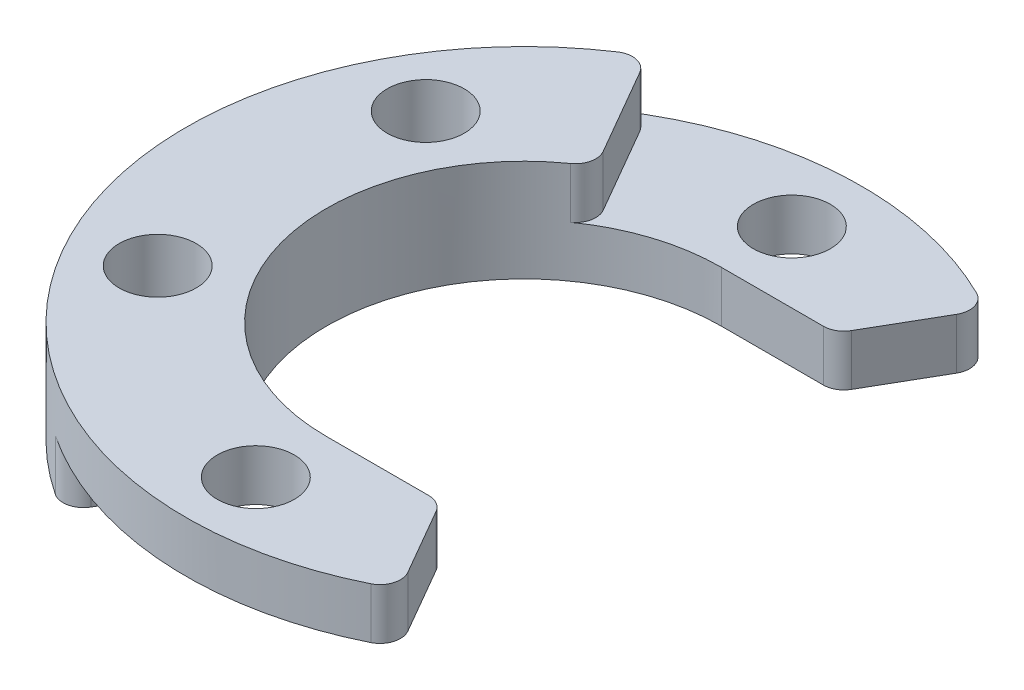
SolidWorks part; units mm, degrees
ref_plane "Front Plane" through (0, 0, 0) normal (0, 0, 1) x (1, 0, 0)
ref_plane "Top Plane" through (0, 0, 0) normal (0, 1, 0) x (1, 0, 0)
ref_plane "Right Plane" through (0, 0, 0) normal (1, 0, 0) x (0, 0, -1)
sketch "Sketch1" plane through (0, 0, 0) normal (0, 1, 0) x (1, 0, 0)
  circle A0 centre (0, 0) radius 42.0965
  circle A1 centre (0, 0) radius 24.5992
  circle A2 centre (0, 33.3931) radius 4.8013
  circle A3 centre (28.9193, 16.6965) radius 4.8013
  circle A4 centre (28.9193, -16.6965) radius 4.8013
  circle A5 centre (0, -33.3931) radius 4.8013
  circle A6 centre (-28.9193, -16.6965) radius 4.8013
  circle A7 centre (-28.9193, 16.6965) radius 4.8013
extrude "Extrude1" add sketch "Sketch1" along normal blind 12.7
sketch "Sketch3" plane through (0, 12.7, 0) normal (0, 1, 0) x (1, 0, 0)
  line L0 (0, 0) -> (28.179, 48.8074)
  line L1 (28.179, 48.8074) -> (52.0996, 15.1016)
  line L2 (52.0996, 15.1016) -> (29.4022, -50.9261)
  line L3 (29.4022, -50.9261) -> (0, 0)
  line L4 (0, 0) -> (0, 44.7323) construction
  dimension "D1" = 30
  dimension "D2" = 30
extrude "Extrude2" cut sketch "Sketch3" against normal through all
sketch "Sketch4" plane through (0, 12.7, 0) normal (0, 1, 0) x (1, 0, 0)
  line L0 (0, 0) -> (-31.6788, 54.8693)
  line L1 (-31.6788, 54.8693) -> (34.1827, 54.8693)
  line L2 (34.1827, 54.8693) -> (0, 0)
  line L3 (0, 0) -> (0, 17.9711) construction
  dimension "D1" = 30
extrude "Extrude3" cut sketch "Sketch4" against normal blind 6.35
sketch "Sketch5" plane through (0, 0, 0) normal (0, -1, 0) x (1, 0, 0)
  line L0 (0, 0) -> (-26.213, 45.4023)
  line L1 (-26.213, 45.4023) -> (26.2151, 52.667)
  line L2 (26.2151, 52.667) -> (26.7481, 5.1638)
  line L3 (0, 0) -> (26.7481, 5.1638)
  line L4 (0, 0) -> (0, 14.917) construction
  dimension "D1" = 30
extrude "Extrude4" cut sketch "Sketch5" against normal blind 6.35
sketch "Sketch6" plane through (0, 0, 0) normal (0, -1, 0) x (1, 0, 0)
  line L0 (0, 33.3931) -> (0, -6.0555) construction
  line L2 (0, 24.5992) -> (38.3103, 24.5992)
  line L3 (0, 24.5992) -> (0, -24.5992)
  line L4 (0, -24.5992) -> (38.3103, -24.5992)
  line L5 (38.3103, 24.5992) -> (38.3103, -24.5992)
  arc A0 (12.2996, 21.3035) -> (-12.2996, 21.3035) centre (0, 0) ccw construction
  arc A1 (-12.2996, 21.3035) -> (12.2996, -21.3035) centre (0, 0) ccw construction
extrude "Extrude5" cut sketch "Sketch6" against normal through all
fillet "Fillet1" radius 2.54 4 edges at (21.0483, 3.175, -36.4566) (14.2024, 3.175, -24.5992) (14.2024, 9.525, 24.5992) (21.0483, 9.525, 36.4566)
fillet "Fillet2" radius 2.54 4 edges at (-21.0483, 9.525, -36.4566) (-12.2996, 9.525, -21.3035) (-12.2996, 3.175, 21.3035) (-21.0483, 3.175, 36.4566)
